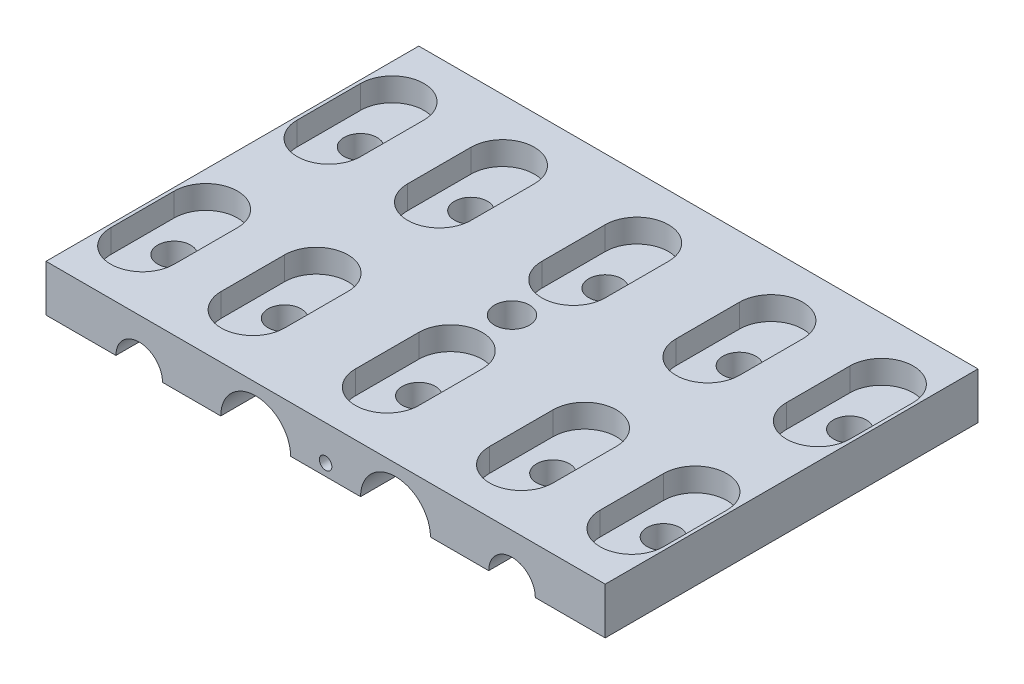
SolidWorks part; units mm, degrees
material "Copper"
ref_plane "Front Plane" through (0, 0, 0) normal (0, 0, 1) x (1, 0, 0)
ref_plane "Top Plane" through (0, 0, 0) normal (0, 1, 0) x (1, 0, 0)
ref_plane "Right Plane" through (0, 0, 0) normal (1, 0, 0) x (0, 0, -1)
sketch "Sketch1" plane through (0, 0, 0) normal (0, 1, 0) x (1, 0, 0)
  line L1 (-38.1, 25.4) -> (38.1, 25.4)
  line L2 (-38.1, 25.4) -> (-38.1, -25.4)
  line L3 (-38.1, -25.4) -> (38.1, -25.4)
  line L4 (38.1, 25.4) -> (38.1, -25.4)
  dimension "D1" = 50.8
  dimension "D2" = 76.2
  dimension "D3" = 38.1
  dimension "D4" = 25.4
extrude "Boss-Extrude1" add sketch "Sketch1" along normal blind 6.35
sketch "Sketch2" plane through (0, 0, 25.4) normal (0, 0, 1) x (1, 0, 0)
  line L0 (-38.1, 0) -> (38.1, 0) construction
  line L1 (-38.1, 6.35) -> (-38.1, 0) construction
  circle A0 centre (-25.4, 0) radius 3.175
  circle A1 centre (25.4, 0) radius 3.175
  dimension "D3" = 6.35
  dimension "D1" = 50.8
  dimension "D2" = 12.7
extrude "Cut-Extrude1" cut sketch "Sketch2" against normal through all
sketch "Sketch3" plane through (0, 0, 25.4) normal (0, 0, 1) x (1, 0, 0)
  line L0 (-22.225, 0) -> (22.225, 0) construction
  circle A0 centre (-9.525, 0) radius 4.7625
  circle A1 centre (9.525, 0) radius 4.7625
  dimension "D1" = 9.525
  dimension "D2" = 19.05
  dimension "D3" = 9.525
extrude "Cut-Extrude2" cut sketch "Sketch3" against normal through all
hole_wizard "#8 Clearance Hole1" positions "Sketch5" profile "Sketch4" hole size "#8" standard "ANSI Inch" end condition through all
sketch "Sketch5" plane through (0, 6.35, 0) normal (0, 1, 0) x (1, 0, 0)
  line L2 (38.1, 25.4) -> (-38.1, 25.4) construction
  line L3 (-38.1, -25.4) -> (38.1, -25.4) construction
  line L4 (-38.1, 25.4) -> (-38.1, -25.4) construction
  line L5 (38.1, -25.4) -> (38.1, 25.4) construction
  point P0 (-33.3375, 12.7)
  point P2 (-33.3375, -12.7)
  point P4 (-18.288, -12.7)
  point P6 (0, -12.7)
  point P8 (18.288, -12.7)
  point P10 (33.3375, -12.7)
  point P12 (33.3375, 12.7)
  point P14 (18.288, 12.7)
  point P16 (0, 12.7)
  point P18 (-18.288, 12.7)
  dimension "D1" = 12.7
  dimension "D2" = 12.7
  dimension "D3" = 4.7625
  dimension "D4" = 4.7625
  dimension "D5" = 19.812
  dimension "D6" = 19.812
sketch "Sketch4" plane through (-33.3375, 6.35, -12.7) normal (1, 0, 0) x (0, 0, 1)
  line L0 (0, 0) -> (0, 6.35)
  line L1 (0, 6.35) -> (2.2479, 6.35)
  line L2 (2.2479, 6.35) -> (2.2479, 0)
  line L5 (2.2479, 0) -> (0, 0)
  line L11 (0, -6.35) -> (0, 107.95) construction
  dimension "Thru Hole Dia." = 4.4958
  dimension "Thru Hole Depth" = 6.35
sketch "Sketch6" plane through (0, 6.35, 0) normal (0, 1, 0) x (1, 0, 0)
  line L0 (-18.288, 17.018) -> (-18.288, 8.382) construction
  line L1 (-13.97, 17.018) -> (-13.97, 8.382)
  line L2 (-22.606, 17.018) -> (-22.606, 8.382)
  line L3 (0, 25.4) -> (0, 0) construction
  line L4 (38.1, 25.4) -> (-38.1, 25.4) construction
  line L5 (38.1, 0) -> (0, 0) construction
  line L6 (38.1, -25.4) -> (38.1, 25.4) construction
  line L7 (18.288, 17.018) -> (18.288, 8.382) construction
  line L8 (13.97, 17.018) -> (13.97, 8.382)
  line L9 (22.606, 17.018) -> (22.606, 8.382)
  line L10 (18.288, -17.018) -> (18.288, -8.382) construction
  line L11 (13.97, -17.018) -> (13.97, -8.382)
  line L12 (22.606, -17.018) -> (22.606, -8.382)
  line L13 (-18.288, -17.018) -> (-18.288, -8.382) construction
  line L14 (-13.97, -17.018) -> (-13.97, -8.382)
  line L15 (-22.606, -17.018) -> (-22.606, -8.382)
  line L16 (0, 17.018) -> (0, 8.382) construction
  line L17 (4.318, 17.018) -> (4.318, 8.382)
  line L18 (-4.318, 17.018) -> (-4.318, 8.382)
  line L19 (0, -17.018) -> (0, -8.382) construction
  line L20 (4.318, -17.018) -> (4.318, -8.382)
  line L21 (-4.318, -17.018) -> (-4.318, -8.382)
  line L22 (-33.3375, 17.018) -> (-33.3375, 8.382) construction
  line L23 (-29.0195, 17.018) -> (-29.0195, 8.382)
  line L24 (-37.6555, 17.018) -> (-37.6555, 8.382)
  line L25 (-33.3375, -17.018) -> (-33.3375, -8.382) construction
  line L26 (-29.0195, -17.018) -> (-29.0195, -8.382)
  line L27 (-37.6555, -17.018) -> (-37.6555, -8.382)
  line L28 (33.3375, 17.018) -> (33.3375, 8.382) construction
  line L29 (29.0195, 17.018) -> (29.0195, 8.382)
  line L30 (37.6555, 17.018) -> (37.6555, 8.382)
  line L31 (33.3375, -17.018) -> (33.3375, -8.382) construction
  line L32 (29.0195, -17.018) -> (29.0195, -8.382)
  line L33 (37.6555, -17.018) -> (37.6555, -8.382)
  arc A0 (-13.97, 17.018) -> (-22.606, 17.018) centre (-18.288, 17.018) ccw
  arc A1 (-22.606, 8.382) -> (-13.97, 8.382) centre (-18.288, 8.382) ccw
  arc A2 (13.97, 17.018) -> (22.606, 17.018) centre (18.288, 17.018) cw
  arc A3 (22.606, 8.382) -> (13.97, 8.382) centre (18.288, 8.382) cw
  arc A4 (13.97, -17.018) -> (22.606, -17.018) centre (18.288, -17.018) ccw
  arc A5 (22.606, -8.382) -> (13.97, -8.382) centre (18.288, -8.382) ccw
  arc A6 (-13.97, -17.018) -> (-22.606, -17.018) centre (-18.288, -17.018) cw
  arc A7 (-22.606, -8.382) -> (-13.97, -8.382) centre (-18.288, -8.382) cw
  arc A11 (4.318, 17.018) -> (-4.318, 17.018) centre (0, 17.018) ccw
  arc A12 (-4.318, 8.382) -> (4.318, 8.382) centre (0, 8.382) ccw
  arc A13 (4.318, -17.018) -> (-4.318, -17.018) centre (0, -17.018) cw
  arc A14 (-4.318, -8.382) -> (4.318, -8.382) centre (0, -8.382) cw
  arc A15 (-29.0195, 17.018) -> (-37.6555, 17.018) centre (-33.3375, 17.018) ccw
  arc A16 (-37.6555, 8.382) -> (-29.0195, 8.382) centre (-33.3375, 8.382) ccw
  arc A17 (-29.0195, -17.018) -> (-37.6555, -17.018) centre (-33.3375, -17.018) cw
  arc A18 (-37.6555, -8.382) -> (-29.0195, -8.382) centre (-33.3375, -8.382) cw
  arc A19 (29.0195, 17.018) -> (37.6555, 17.018) centre (33.3375, 17.018) cw
  arc A20 (37.6555, 8.382) -> (29.0195, 8.382) centre (33.3375, 8.382) cw
  arc A21 (29.0195, -17.018) -> (37.6555, -17.018) centre (33.3375, -17.018) ccw
  arc A22 (37.6555, -8.382) -> (29.0195, -8.382) centre (33.3375, -8.382) ccw
  point P3 (-18.288, 12.7)
  point P18 (18.288, 12.7)
  point P25 (18.288, -12.7)
  point P32 (-18.288, -12.7)
  point P39 (0, 12.7)
  point P46 (0, -12.7)
  point P54 (-33.3375, 12.7)
  point P61 (-33.3375, -12.7)
  point P68 (33.3375, 12.7)
  point P75 (33.3375, -12.7)
  dimension "D1" = 8.636
  dimension "D2" = 12.7
  dimension "D3" = 8.636
  dimension "D4" = 12.7
  dimension "D5" = 8.636
  dimension "D6" = 8.636
  dimension "D7" = 12.7
  dimension "D8" = 8.636
  dimension "D9" = 8.636
extrude "Cut-Extrude3" cut sketch "Sketch6" against normal blind 3.175
sketch "Sketch7" plane through (0, 6.35, 0) normal (0, 1, 0) x (1, 0, 0)
  circle A0 centre (0, 0) radius 2.3813
  dimension "D1" = 4.7625
extrude "Cut-Extrude4" cut sketch "Sketch7" against normal through all
sketch "Sketch8" plane through (0, 0, 25.4) normal (0, 0, 1) x (1, 0, 0)
  line L0 (-4.7625, 0) -> (4.7625, 0) construction
  circle A0 centre (0, 1.5875) radius 0.8509
  dimension "D2" = 1.7018
  dimension "D1" = 1.5875
extrude "Cut-Extrude5" cut sketch "Sketch8" against normal blind 9.525
